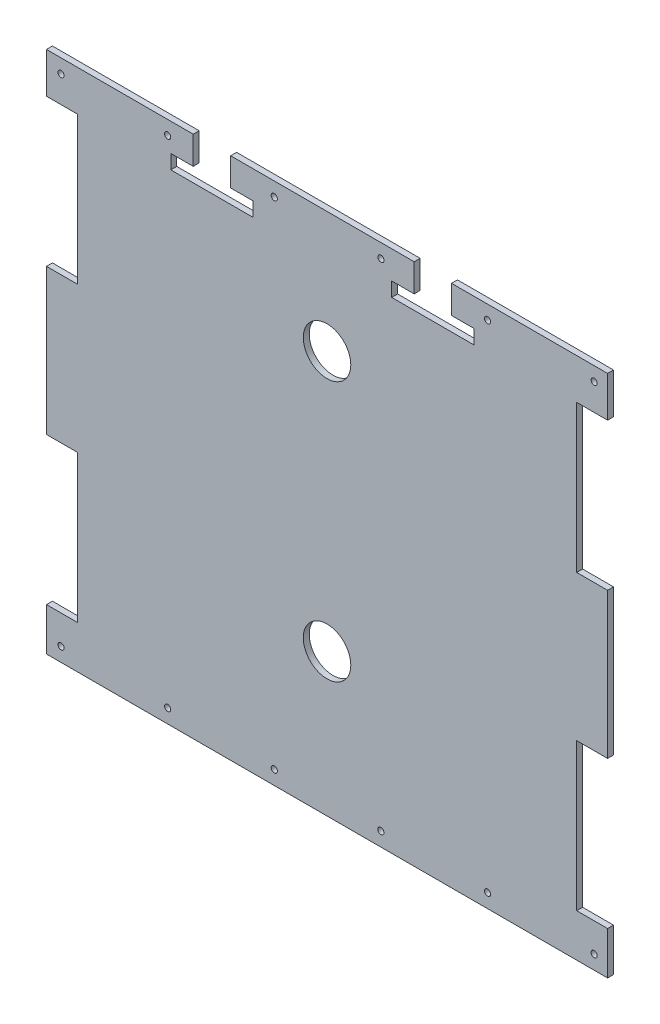
SolidWorks part; units mm, degrees
material "PBT General Purpose"
ref_plane "Front" through (0, 0, 0) normal (0, 0, 1) x (1, 0, 0)
ref_plane "Top" through (0, 0, 0) normal (0, 1, 0) x (1, 0, 0)
ref_plane "Right" through (0, 0, 0) normal (1, 0, 0) x (0, 0, -1)
sketch "Sketch5" plane through (0, 0, 0) normal (0, 0, 1) x (1, 0, 0)
  line L0 (47.1246, -7.4523) -> (30.6146, -7.4523)
  line L1 (-252.8494, 249.5587) -> (-174.4024, 249.5587)
  line L2 (-252.8494, 249.5587) -> (-252.8494, 227.8859)
  line L3 (-252.8494, -30.3493) -> (47.1246, -30.3493)
  line L4 (47.1246, 249.5587) -> (47.1246, 227.8859)
  line L5 (30.6146, -7.4523) -> (30.6146, 71.2877)
  line L6 (30.6146, 71.2877) -> (47.1246, 71.2877)
  line L8 (47.1246, -7.4523) -> (47.1246, -30.3493)
  line L9 (47.1246, 149.1459) -> (30.6146, 149.1459)
  line L10 (30.6146, 149.1459) -> (30.6146, 227.8859)
  line L11 (30.6146, 227.8859) -> (47.1246, 227.8859)
  line L13 (47.1246, 149.1459) -> (47.1246, 71.2877)
  line L14 (-252.8494, 227.8859) -> (-236.3394, 227.8859)
  line L15 (-236.3394, 227.8859) -> (-236.3394, 149.1459)
  line L16 (-236.3394, 149.1459) -> (-252.8494, 149.1459)
  line L18 (-252.8494, 149.1459) -> (-252.8494, 71.2877)
  line L19 (-252.8494, 71.2877) -> (-236.3394, 71.2877)
  line L20 (-236.3394, 71.2877) -> (-236.3394, -7.4523)
  line L21 (-236.3394, -7.4523) -> (-252.8494, -7.4523)
  line L23 (-252.8494, -7.4523) -> (-252.8494, -30.3493)
  line L24 (47.1246, -22.8907) -> (-72.4065, -22.8907) construction
  line L25 (-252.8494, 242.1016) -> (-174.4024, 242.1016) construction
  line L26 (-75.7065, -22.8907) -> (-252.8494, -22.8907) construction
  line L27 (-56.3024, 249.5587) -> (-56.3024, 234.6507)
  line L28 (-56.3024, 227.0307) -> (-36.3024, 227.0307)
  line L29 (-36.3024, 234.6507) -> (-36.3024, 249.5587)
  line L31 (-174.4024, 249.5587) -> (-174.4024, 234.6507)
  line L32 (-174.4024, 227.0307) -> (-154.4024, 227.0307)
  line L33 (-154.4024, 234.6507) -> (-154.4024, 249.5587)
  line L35 (-154.4024, 249.5587) -> (-56.3024, 249.5587)
  line L36 (-154.4024, 242.1016) -> (-56.3024, 242.1016) construction
  line L37 (-36.3024, 249.5587) -> (47.1246, 249.5587)
  line L38 (-36.3024, 242.1016) -> (47.1246, 242.1016) construction
  line L39 (-36.3024, 234.6507) -> (-24.3024, 234.6507)
  line L40 (-252.8494, 234.6507) -> (47.1506, 234.6507) construction
  line L41 (-24.3024, 234.6507) -> (-24.3024, 227.0307)
  line L42 (-24.3024, 227.0307) -> (-36.3024, 227.0307)
  line L43 (-56.3024, 234.6507) -> (-68.3024, 234.6507)
  line L44 (-174.4024, 234.6507) -> (-186.4024, 234.6507)
  line L45 (-54.6336, 234.6507) -> (-154.6336, 234.6507) construction
  line L46 (-68.3024, 234.6507) -> (-68.3024, 227.0307)
  line L47 (-68.3024, 227.0307) -> (-56.3024, 227.0307)
  line L48 (-186.4024, 234.6507) -> (-186.4024, 227.0307)
  line L49 (-186.4024, 227.0307) -> (-174.4024, 227.0307)
  line L50 (-154.4024, 234.6507) -> (-142.4024, 234.6507)
  line L51 (-142.4024, 234.6507) -> (-142.4024, 227.0307)
  line L52 (-142.4024, 227.0307) -> (-154.4024, 227.0307)
  circle A8 centre (39.9435, -22.8907) radius 1.65
  circle A10 centre (-17.0565, -22.8907) radius 1.65
  circle A11 centre (-74.0565, -22.8907) radius 1.65
  circle A12 centre (-131.0565, -22.8907) radius 1.65
  circle A13 centre (-188.0565, -22.8907) radius 1.65
  circle A14 centre (-245.0565, -22.8907) radius 1.65
  circle A15 centre (39.9435, 242.1016) radius 1.65
  circle A16 centre (-17.0565, 242.1016) radius 1.65
  circle A17 centre (-74.0565, 242.1016) radius 1.65
  circle A18 centre (-131.0565, 242.1016) radius 1.65
  circle A19 centre (-188.0565, 242.1016) radius 1.65
  circle A20 centre (-245.0565, 242.1016) radius 1.65
  circle A22 centre (-102.8624, 184.8543) radius 12.7
  circle A23 centre (-102.8624, 45.8507) radius 12.7
  point P12 (38.8696, 149.1459)
  dimension "D10" = 3.3
  dimension "D12" = 3.3
  dimension "D14" = 25.4
  dimension "D15" = 25.4
  dimension "D1" = 299.974
  dimension "D2" = 279.908
  dimension "D3" = 16.51
  dimension "D4" = 16.51
  dimension "D5" = 16.51
  dimension "D6" = 78.74
  dimension "D7" = 78.74
  dimension "D8" = 78.74
  dimension "D9" = 16.51
  dimension "D16" = 76.2
  dimension "D17" = 20
  dimension "D19" = 12
  dimension "D20" = 12
  dimension "D21" = 12
  dimension "D22" = 12
  dimension "D23" = 7.62
  dimension "D11" = 6
  dimension "D13" = 6
extrude "Boss-Extrude1" add sketch "Sketch5" along normal blind 3.175
